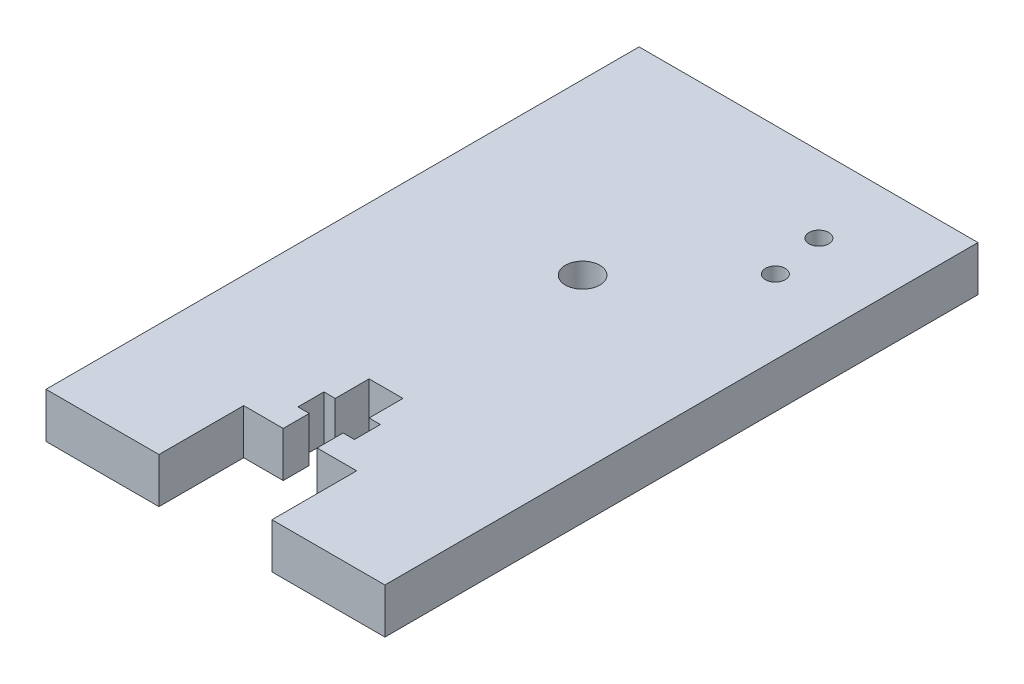
SolidWorks part; units mm, degrees
ref_plane "Front Plane" through (0, 0, 0) normal (0, 0, 1) x (1, 0, 0)
ref_plane "Top Plane" through (0, 0, 0) normal (0, 1, 0) x (1, 0, 0)
ref_plane "Right Plane" through (0, 0, 0) normal (1, 0, 0) x (0, 0, -1)
sketch "Sketch1" plane through (0, 0, 0) normal (0, 1, 0) x (1, 0, 0)
  line L0 (-10, -37) -> (-10, -22)
  line L1 (10, -37) -> (30, -37)
  line L2 (30, -37) -> (30, 38)
  line L3 (30, 38) -> (30, 58)
  line L4 (-30, -37) -> (-30, 38)
  line L5 (-5, -12.8) -> (-3, -12.8)
  line L6 (3, -12.8) -> (3, -6.8)
  line L8 (10, -37) -> (10, -22)
  line L9 (-10, -37) -> (-30, -37)
  line L10 (10, -22) -> (3, -22)
  line L11 (3, -6.8) -> (-3, -6.8)
  line L12 (3, -17.4) -> (3, -22)
  line L13 (-3, -17.4) -> (-3, -22)
  line L14 (-3, -22) -> (-10, -22)
  line L15 (5, -12.8) -> (5, -17.4)
  line L16 (5, -17.4) -> (3, -17.4)
  line L17 (-5, -17.4) -> (-3, -17.4)
  line L18 (-5, -12.8) -> (-5, -17.4)
  line L19 (-3, -6.8) -> (-3, -12.8)
  line L20 (3, -12.8) -> (5, -12.8)
  line L21 (-30, 58) -> (-30, 38)
  line L22 (-30, 58) -> (-30, 68)
  line L23 (30, 58) -> (30, 68)
  line L24 (30, 68) -> (-30, 68)
  circle A0 centre (0, 28) radius 3.05
  circle A2 centre (16.8944, 45.2323) radius 1.75
  circle A4 centre (15.2448, 54.588) radius 1.75
extrude "Boss-Extrude1" add sketch "Sketch1" along normal blind 8
